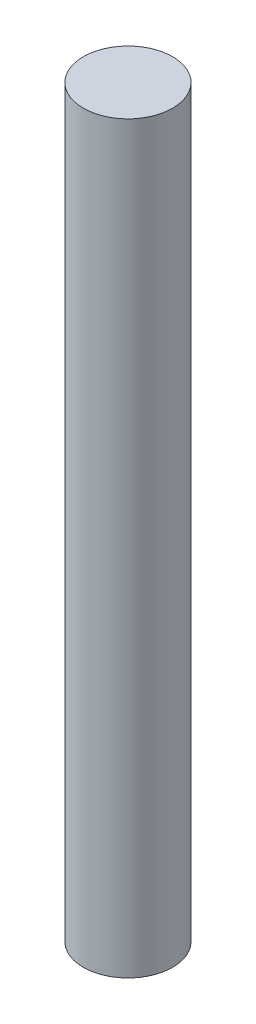
SolidWorks part; units mm, degrees
material "Brass"
ref_plane "Front Plane" through (0, 0, 0) normal (0, 0, 1) x (1, 0, 0)
ref_plane "Top Plane" through (0, 0, 0) normal (0, 1, 0) x (1, 0, 0)
ref_plane "Right Plane" through (0, 0, 0) normal (1, 0, 0) x (0, 0, -1)
sketch "Sketch1" plane through (0, 0, 0) normal (0, 1, 0) x (1, 0, 0)
  circle A0 centre (0, 0) radius 1.8
  dimension "D1" = 3.6
extrude "Boss-Extrude1" add sketch "Sketch1" along normal blind 30
